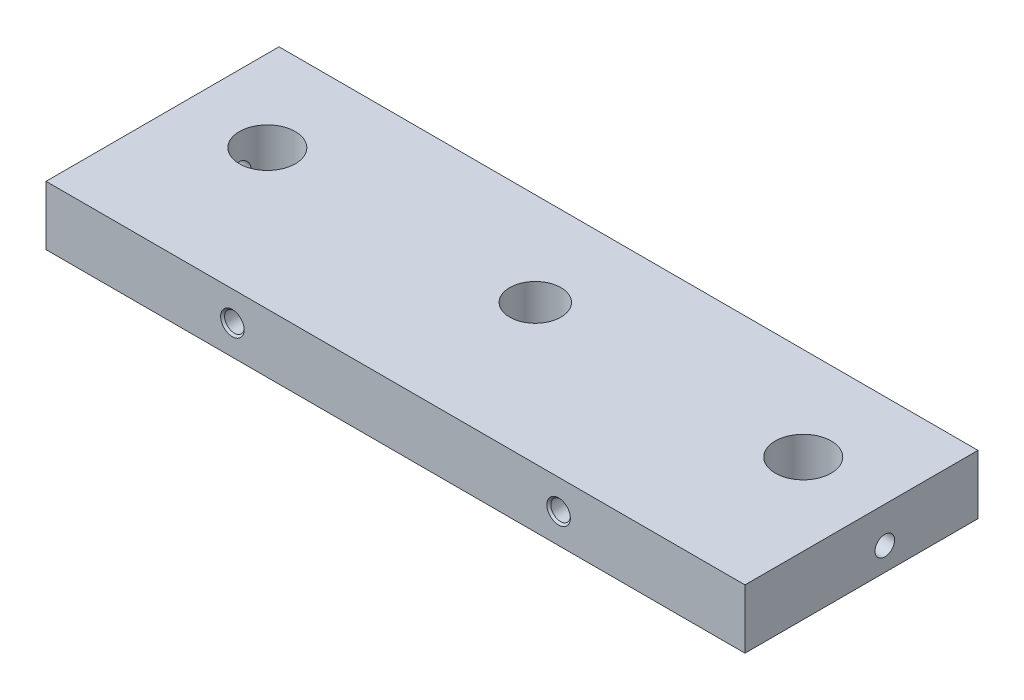
SolidWorks part; units mm, degrees
material "Liga 1060"
ref_plane "Frontal" through (0, 0, 0) normal (0, 0, 1) x (1, 0, 0)
ref_plane "Superior" through (0, 0, 0) normal (0, 1, 0) x (1, 0, 0)
ref_plane "Direito" through (0, 0, 0) normal (1, 0, 0) x (0, 0, -1)
sketch "Esboço1" plane through (0, 0, 0) normal (0, 1, 0) x (1, 0, 0)
  line L1 (-75, 20) -> (75, 20)
  line L2 (-75, 20) -> (-75, -20)
  line L3 (-75, -20) -> (75, -20)
  line L4 (75, 20) -> (75, -20)
  line L5 (-75, 20) -> (75, -20) construction
  line L6 (-75, -20) -> (75, 20) construction
  circle A0 centre (0, 0) radius 2.5
  point P0 (0, 0)
  dimension "D3" = 5
  dimension "D1" = 40
  dimension "D2" = 150
extrude "Ressalto-extrusão1" add sketch "Esboço1" along normal blind 12.7
sketch "Esboço2" plane through (0, 12.7, 0) normal (0, 1, 0) x (1, 0, 0)
  circle A0 centre (0, 0) radius 5.5
  dimension "D1" = 11
extrude "Corte-extrusão1" cut sketch "Esboço2" against normal blind 8
sketch "Esboço3" plane through (0, 12.7, 0) normal (0, 1, 0) x (1, 0, 0)
  line L0 (-75, 20) -> (-75, -20) construction
  line L1 (75, -20) -> (75, 20) construction
  line L2 (75, 20) -> (-75, 20) construction
  circle A0 centre (-57.5, 0) radius 6
  circle A1 centre (57.5, 0) radius 6
  dimension "D3" = 12
  dimension "D4" = 12
  dimension "D6" = 20
  dimension "D1" = 17.5
  dimension "D2" = 17.5
  dimension "D5" = 20
extrude "Corte-extrusão3" cut sketch "Esboço3" against normal through all
hole_wizard "Furo roscado de M51" positions "Esboço5" profile "Esboço6" tap size "M5" standard "ISO"
sketch "Esboço5" plane through (75, 0, 0) normal (1, 0, 0) x (0, 0, -1)
  line L0 (-20, 0) -> (20, 0) construction
  line L1 (20, 12.7) -> (20, 0) construction
  point P0 (0, 5)
  dimension "D1" = 5
  dimension "D2" = 20
sketch "Esboço6" plane through (75, 5, 0) normal (0, 1, 0) x (0, 0, -1)
  line L0 (0, 0) -> (0, 13.2618)
  line L1 (0, 13.2618) -> (2.1, 12)
  line L2 (2.1, 12) -> (2.1, 0)
  line L5 (2.1, 0) -> (0, 0)
  line L10 (0, 13.2618) -> (-2.1, 12) construction
  line L11 (0, -6.35) -> (0, 107.95) construction
  dimension "Tap Drill Dia." = 4.2
  dimension "Tap Drill Depth" = 12
  dimension "Drill Angle" = 118
cosmetic thread "Rosca de furo1" parameters "D1"=10, "D2"=5
mirror "Espelhar1" about plane through (0, 0, 0) normal (1, 0, 0) of "Furo roscado de M51"
sketch "Esboço7" plane through (0, 12.7, 0) normal (0, 1, 0) x (1, 0, 0)
  line L0 (-75, -20) -> (75, -20)
  line L1 (-75, -20) -> (-75, -30)
  line L2 (75, -20) -> (75, -30)
  line L3 (-75, -30) -> (75, -30)
  dimension "D1" = 10
extrude "Ressalto-extrusão2" add sketch "Esboço7" against normal up to surface (12.7 mm away) up to face at (57.5, 0, 6)
sketch "Esboço8" plane through (0, 0, 30) normal (0, 0, 1) x (1, 0, 0)
  line L0 (35, 0) -> (35, 12.7) construction
  line L1 (75, 0) -> (-75, 0) construction
  line L2 (-75, 12.7) -> (75, 12.7) construction
  line L3 (-35, 0) -> (-35, 12.7) construction
  line L4 (75, 0) -> (75, 12.7) construction
  line L5 (-75, 0) -> (-75, 12.7) construction
  circle A0 centre (35, 6.35) radius 2
  circle A1 centre (-35, 6.35) radius 2
  dimension "D3" = 4
  dimension "D1" = 40
  dimension "D2" = 40
extrude "Corte-extrusão4" cut sketch "Esboço8" against normal blind 10
hole_wizard "Furo roscado de M54" positions "Esboço11" profile "Esboço12" tap size "M5" standard "ISO"
sketch "Esboço11" plane through (0, 0, 30) normal (0, 0, 1) x (1, 0, 0)
  point P0 (-35, 6.35)
sketch "Esboço12" plane through (-35, 6.35, 30) normal (1, 0, 0) x (0, -1, 0)
  line L0 (0, 0) -> (0, 13.6618)
  line L1 (0, 13.6618) -> (2.1, 12.4)
  line L2 (2.1, 12.4) -> (2.1, 0.425)
  line L3 (2.1, 0.425) -> (2.525, 0)
  line L5 (2.525, 0) -> (0, 0)
  line L6 (-2.1, 0.425) -> (-2.525, 0) construction
  line L10 (0, 13.6618) -> (-2.1, 12.4) construction
  line L11 (0, -6.35) -> (0, 107.95) construction
  dimension "Tap Drill Dia." = 4.2
  dimension "Tap Drill Depth" = 12.4
  dimension "Near C'Sink Dia." = 5.05
  dimension "Near C'Sink Angle" = 90
  dimension "Drill Angle" = 118
cosmetic thread "Rosca de furo4" parameters "D1"=10, "D2"=5
hole_wizard "Furo roscado de M55" positions "Esboço13" profile "Esboço14" tap size "M5" standard "ISO"
sketch "Esboço13" plane through (0, 0, 30) normal (0, 0, 1) x (1, 0, 0)
  point P0 (35, 6.35)
sketch "Esboço14" plane through (35, 6.35, 30) normal (1, 0, 0) x (0, -1, 0)
  line L0 (0, 0) -> (0, 13.6618)
  line L1 (0, 13.6618) -> (2.1, 12.4)
  line L2 (2.1, 12.4) -> (2.1, 0.425)
  line L3 (2.1, 0.425) -> (2.525, 0)
  line L5 (2.525, 0) -> (0, 0)
  line L6 (-2.1, 0.425) -> (-2.525, 0) construction
  line L10 (0, 13.6618) -> (-2.1, 12.4) construction
  line L11 (0, -6.35) -> (0, 107.95) construction
  dimension "Tap Drill Dia." = 4.2
  dimension "Tap Drill Depth" = 12.4
  dimension "Near C'Sink Dia." = 5.05
  dimension "Near C'Sink Angle" = 90
  dimension "Drill Angle" = 118
cosmetic thread "Rosca de furo5" parameters "D1"=10, "D2"=5
